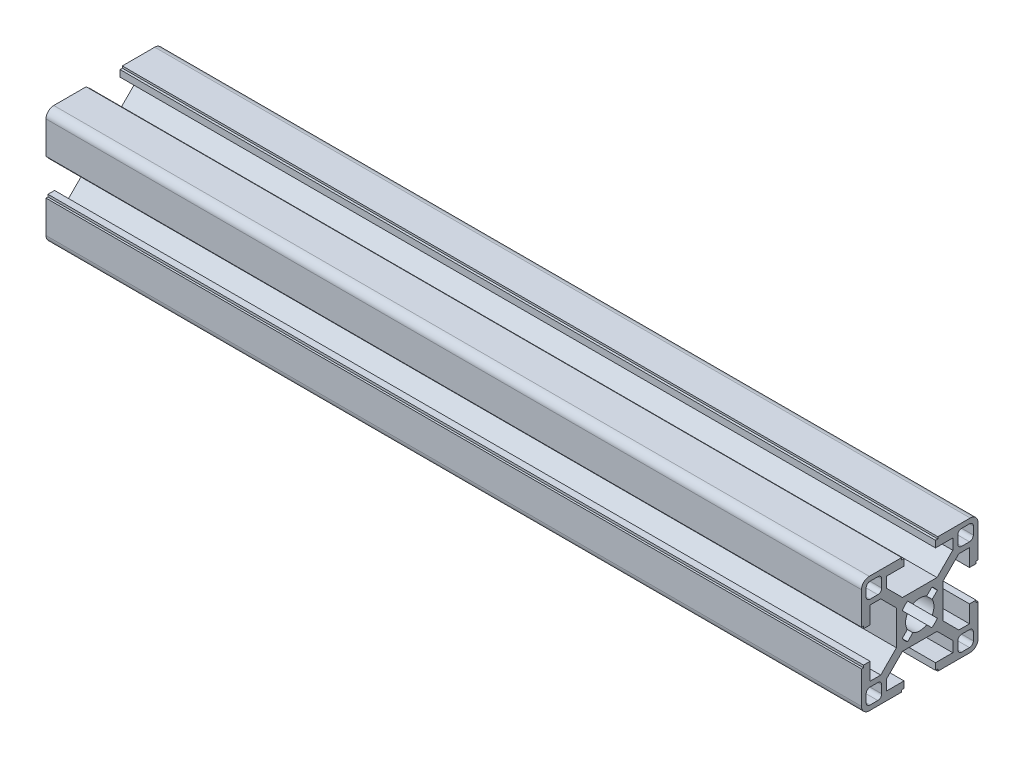
SolidWorks part; units mm, degrees
ref_plane "Ebene vorne" through (0, 0, 0) normal (0, 0, 1) x (1, 0, 0)
ref_plane "Ebene oben" through (0, 0, 0) normal (0, 1, 0) x (1, 0, 0)
ref_plane "Ebene rechts" through (0, 0, 0) normal (1, 0, 0) x (0, 0, -1)
sketch "Skizze1" plane through (0, 0, 0) normal (1, 0, 0) x (0, 0, -1)
  line L0 (8.5, 10.0556) -> (4.4444, 6)
  line L1 (13, 15) -> (-13, 15)
  line L2 (15, 13) -> (15, -13)
  line L3 (13, -15) -> (-13, -15)
  line L4 (-15, 13) -> (-15, -13)
  line L5 (15, 15) -> (-15, -15) construction
  line L6 (15, -15) -> (-15, 15) construction
  line L7 (6, 6) -> (-6, 6)
  line L8 (6, 6) -> (6, -6)
  line L9 (6, -6) -> (-6, -6)
  line L10 (-6, 6) -> (-6, -6)
  line L11 (6, 6) -> (-6, -6) construction
  line L12 (6, -6) -> (-6, 6) construction
  line L13 (8.5, 12.8) -> (-8.5, 12.8)
  line L14 (8.5, 12.8) -> (8.5, 6)
  line L15 (8.5, 6) -> (-8.5, 6)
  line L16 (-8.5, 12.8) -> (-8.5, 6)
  line L17 (4.05, 15) -> (-4.05, 15)
  line L18 (4.05, 15) -> (4.05, 12.8)
  line L19 (4.05, 12.8) -> (-4.05, 12.8)
  line L20 (-4.05, 15) -> (-4.05, 12.8)
  line L21 (-8.5, 10.0556) -> (-4.4444, 6)
  line L22 (3.1172, 4.5314) -> (1.7751, 3.1893)
  line L23 (-3.1172, 4.5314) -> (-1.7751, 3.1893)
  line L24 (15, -4.05) -> (12.8, -4.05)
  line L25 (4.05, 15) -> (4.6516, 15)
  line L26 (4.05, 15) -> (4.05, 14.5)
  line L27 (4.05, 14.5) -> (4.6516, 14.5)
  line L28 (4.6516, 15) -> (4.6516, 14.5)
  line L29 (-4.05, 15) -> (-4.6516, 15)
  line L30 (-4.05, 15) -> (-4.05, 14.5)
  line L31 (-4.05, 14.5) -> (-4.6516, 14.5)
  line L32 (-4.6516, 15) -> (-4.6516, 14.5)
  line L33 (15, -4.6516) -> (14.5, -4.6516)
  line L34 (14.5, -4.05) -> (14.5, -4.6516)
  line L35 (14.5, 4.05) -> (14.5, 4.6516)
  line L36 (15, 4.6516) -> (14.5, 4.6516)
  line L37 (15, 4.05) -> (12.8, 4.05)
  line L38 (12.8, 8.5) -> (6, 8.5)
  line L39 (12.8, -8.5) -> (12.8, 8.5)
  line L40 (12.8, -8.5) -> (6, -8.5)
  line L41 (10.0556, -8.5) -> (6, -4.4444)
  line L42 (10.0556, 8.5) -> (6, 4.4444)
  line L43 (4.5314, -3.1172) -> (3.1893, -1.7751)
  line L44 (4.5314, 3.1172) -> (3.1893, 1.7751)
  line L45 (-4.05, -15) -> (-4.05, -12.8)
  line L46 (-4.6516, -15) -> (-4.6516, -14.5)
  line L47 (-4.05, -14.5) -> (-4.6516, -14.5)
  line L48 (4.05, -14.5) -> (4.6516, -14.5)
  line L49 (4.6516, -15) -> (4.6516, -14.5)
  line L50 (4.05, -15) -> (4.05, -12.8)
  line L51 (8.5, -12.8) -> (8.5, -6)
  line L52 (-8.5, -12.8) -> (8.5, -12.8)
  line L53 (-8.5, -12.8) -> (-8.5, -6)
  line L54 (-8.5, -10.0556) -> (-4.4444, -6)
  line L55 (8.5, -10.0556) -> (4.4444, -6)
  line L56 (-3.1172, -4.5314) -> (-1.7751, -3.1893)
  line L57 (3.1172, -4.5314) -> (1.7751, -3.1893)
  line L58 (-15, 4.05) -> (-12.8, 4.05)
  line L59 (-15, 4.6516) -> (-14.5, 4.6516)
  line L60 (-14.5, 4.05) -> (-14.5, 4.6516)
  line L61 (-14.5, -4.05) -> (-14.5, -4.6516)
  line L62 (-15, -4.6516) -> (-14.5, -4.6516)
  line L63 (-15, -4.05) -> (-12.8, -4.05)
  line L64 (-12.8, -8.5) -> (-6, -8.5)
  line L65 (-12.8, 8.5) -> (-12.8, -8.5)
  line L66 (-12.8, 8.5) -> (-6, 8.5)
  line L67 (-10.0556, 8.5) -> (-6, 4.4444)
  line L68 (-10.0556, -8.5) -> (-6, -4.4444)
  line L69 (-4.5314, 3.1172) -> (-3.1893, 1.7751)
  line L70 (-4.5314, -3.1172) -> (-3.1893, -1.7751)
  line L71 (6, -8.5) -> (6, 8.5)
  line L72 (-8.5, -6) -> (8.5, -6)
  line L73 (-6, 8.5) -> (-6, -8.5)
  line L75 (12.8, 13.8) -> (10.8, 13.8)
  line L76 (13.8, 12.8) -> (13.8, 10.8)
  line L77 (12.8, 9.8) -> (10.8, 9.8)
  line L78 (9.8, 12.8) -> (9.8, 10.8)
  line L79 (13.8, 13.8) -> (9.8, 9.8) construction
  line L80 (13.8, 9.8) -> (9.8, 13.8) construction
  line L81 (-10.8, 13.8) -> (-12.8, 13.8)
  line L82 (-9.8, 12.8) -> (-9.8, 10.8)
  line L83 (-10.8, 9.8) -> (-12.8, 9.8)
  line L84 (-13.8, 12.8) -> (-13.8, 10.8)
  line L85 (-9.8, 13.8) -> (-13.8, 9.8) construction
  line L86 (-9.8, 9.8) -> (-13.8, 13.8) construction
  line L87 (12.8, -9.8) -> (10.8, -9.8)
  line L88 (13.8, -10.8) -> (13.8, -12.8)
  line L89 (12.8, -13.8) -> (10.8, -13.8)
  line L90 (9.8, -10.8) -> (9.8, -12.8)
  line L91 (13.8, -9.8) -> (9.8, -13.8) construction
  line L92 (13.8, -13.8) -> (9.8, -9.8) construction
  line L93 (-10.8, -9.8) -> (-12.8, -9.8)
  line L94 (-9.8, -10.8) -> (-9.8, -12.8)
  line L95 (-10.8, -13.8) -> (-12.8, -13.8)
  line L96 (-13.8, -10.8) -> (-13.8, -12.8)
  line L97 (-9.8, -9.8) -> (-13.8, -13.8) construction
  line L98 (-9.8, -13.8) -> (-13.8, -9.8) construction
  arc A0 (13, -15) -> (15, -13) centre (13, -13) ccw
  arc A1 (-13, -15) -> (-15, -13) centre (-13, -13) cw
  arc A2 (-15, 13) -> (-13, 15) centre (-13, 13) cw
  arc A3 (13, 15) -> (15, 13) centre (13, 13) cw
  circle A4 centre (0, 0) radius 3.65
  circle A5 centre (0, 0) radius 5.5
  circle A6 centre (0, 0) radius 3.65
  circle A7 centre (0, 0) radius 3.65
  circle A8 centre (0, 0) radius 3.65
  arc A9 (12.8, -13.8) -> (13.8, -12.8) centre (12.8, -12.8) ccw
  arc A10 (13.8, -10.8) -> (12.8, -9.8) centre (12.8, -10.8) ccw
  arc A11 (9.8, -12.8) -> (10.8, -13.8) centre (10.8, -12.8) ccw
  arc A12 (9.8, -10.8) -> (10.8, -9.8) centre (10.8, -10.8) cw
  arc A13 (-10.8, -13.8) -> (-9.8, -12.8) centre (-10.8, -12.8) ccw
  arc A14 (-10.8, -9.8) -> (-9.8, -10.8) centre (-10.8, -10.8) cw
  arc A15 (-13.8, -12.8) -> (-12.8, -13.8) centre (-12.8, -12.8) ccw
  arc A16 (-13.8, -10.8) -> (-12.8, -9.8) centre (-12.8, -10.8) cw
  arc A17 (-12.8, 9.8) -> (-13.8, 10.8) centre (-12.8, 10.8) cw
  arc A18 (-10.8, 9.8) -> (-9.8, 10.8) centre (-10.8, 10.8) ccw
  arc A19 (-13.8, 12.8) -> (-12.8, 13.8) centre (-12.8, 12.8) cw
  arc A20 (-10.8, 13.8) -> (-9.8, 12.8) centre (-10.8, 12.8) cw
  arc A21 (13.8, 10.8) -> (12.8, 9.8) centre (12.8, 10.8) cw
  arc A22 (10.8, 9.8) -> (9.8, 10.8) centre (10.8, 10.8) cw
  arc A23 (10.8, 13.8) -> (9.8, 12.8) centre (10.8, 12.8) ccw
  arc A24 (12.8, 13.8) -> (13.8, 12.8) centre (12.8, 12.8) cw
  point P0 (0, 0)
  point P33 (0, 12.8)
  point P34 (0, 15)
  point P36 (0, 12.8)
  point P50 (11.8, 11.8)
  point P122 (0, 0)
  point P125 (-11.8, 11.8)
  point P129 (0, 0)
  point P131 (11.8, -11.8)
  point P136 (-11.8, -11.8)
  dimension "D2" = 2
  dimension "D3" = 7.3
  dimension "D4" = 11
  dimension "D20" = 1
  dimension "D1" = 30
  dimension "D5" = 12
  dimension "D6" = 17
  dimension "D7" = 8.1
  dimension "D8" = 2.2
  dimension "D9" = 9
  dimension "D10" = 1.1
  dimension "D11" = 1.1
  dimension "D12" = 1
  dimension "D13" = 1
  dimension "D14" = 0.5
  dimension "D15" = 0.6016
  dimension "D18" = 4
  dimension "D19" = 1.2
  dimension "D16" = 4
  dimension "D17" = 4
extrude "Aufsatz-Linear austragen1" add sketch "Skizze1" along normal blind 280 contours A3 L1 L28 L27 L18 L13 L14 L38 L39 L37 L35 L36 L2 | L42 L38 L14 | L71 L15 L42 L14 L38 L0 | L42 L15 L8 | L7 L71 L0 | L38 L14 L0 | L7 L15 L10 L9 L8 A5 | L43 A5 L44 A4 | L22 A5 L23 A4 | L69 A5 L70 A4 | L56 A5 L57 A4 | L3 A0 L2 L33 L34 L24 L39 L40 L51 L52 L50 L48 L49 | L51 L40 L41 | L72 L71 L55 L40 L51 L41 | L8 L72 L41 | L55 L71 L9 | L55 L51 L40 | L73 L72 L68 L53 L64 L54 | L68 L72 L10 | L9 L73 L54 | L68 L64 L53 | L64 L53 L54 | A1 L3 L46 L47 L45 L52 L53 L64 L65 L63 L61 L62 L4 | A2 L4 L59 L60 L58 L65 L66 L16 L13 L20 L31 L32 L1 | L66 L67 L16 | L16 L66 L21 | L73 L21 L66 L16 L67 L15 | L21 L73 L15 | L15 L67 L10
scale "Scale1" scale about centroid uniform scaling no x scale factor 1 y scale factor 1.333333 z scale factor 1.333333
